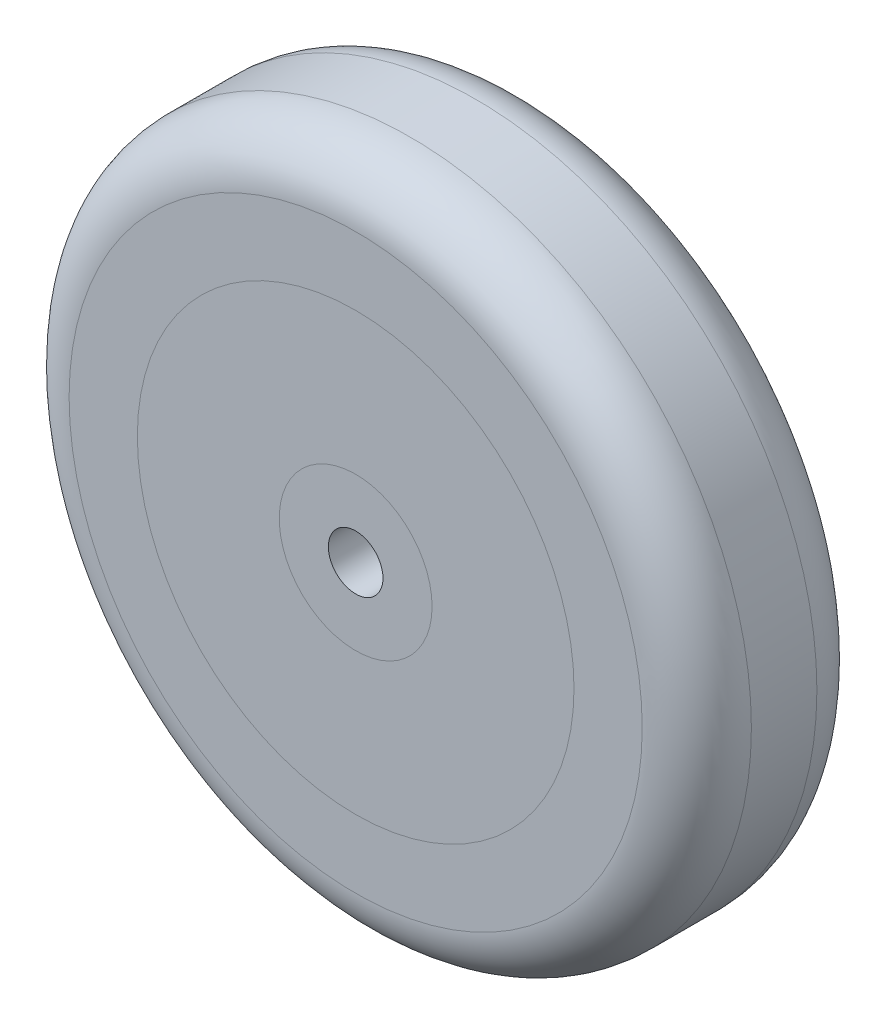
SolidWorks part; units mm, degrees
ref_plane "Front Plane" through (0, 0, 0) normal (0, 0, 1) x (1, 0, 0)
ref_plane "Top Plane" through (0, 0, 0) normal (0, 1, 0) x (1, 0, 0)
ref_plane "Right Plane" through (0, 0, 0) normal (1, 0, 0) x (0, 0, -1)
sketch "Sketch1" plane through (0, 0, 0) normal (0, 0, 1) x (1, 0, 0)
  circle A0 centre (0, 0) radius 14
  circle A1 centre (0, 0) radius 40
  dimension "D1" = 28
  dimension "D2" = 80
extrude "Boss-Extrude1" add sketch "Sketch1" along normal blind 32
sketch "Sketch2" plane through (0, 0, 32) normal (0, 0, 1) x (1, 0, 0)
  circle A0 centre (0, 0) radius 40
  circle A1 centre (0, 0) radius 62.5
  circle A2 centre (0, 0) radius 40 construction
  dimension "D1" = 125
extrude "Boss-Extrude2" add sketch "Sketch2" against normal up to surface (32 mm away) separate body up to face at (40, 0, 0)
sketch "Sketch3" plane through (0, 0, 32) normal (0, 0, 1) x (1, 0, 0)
  circle A0 centre (0, 0) radius 14
  circle A1 centre (0, 0) radius 5
  circle A2 centre (0, 0) radius 14 construction
  dimension "D1" = 10
extrude "Boss-Extrude3" add sketch "Sketch3" against normal up to surface (32 mm away) separate body up to face at (40, 0, 0)
fillet "Fillet1" radius 10 2 edges at (62.5, 0, 0) (62.5, 0, 32)
